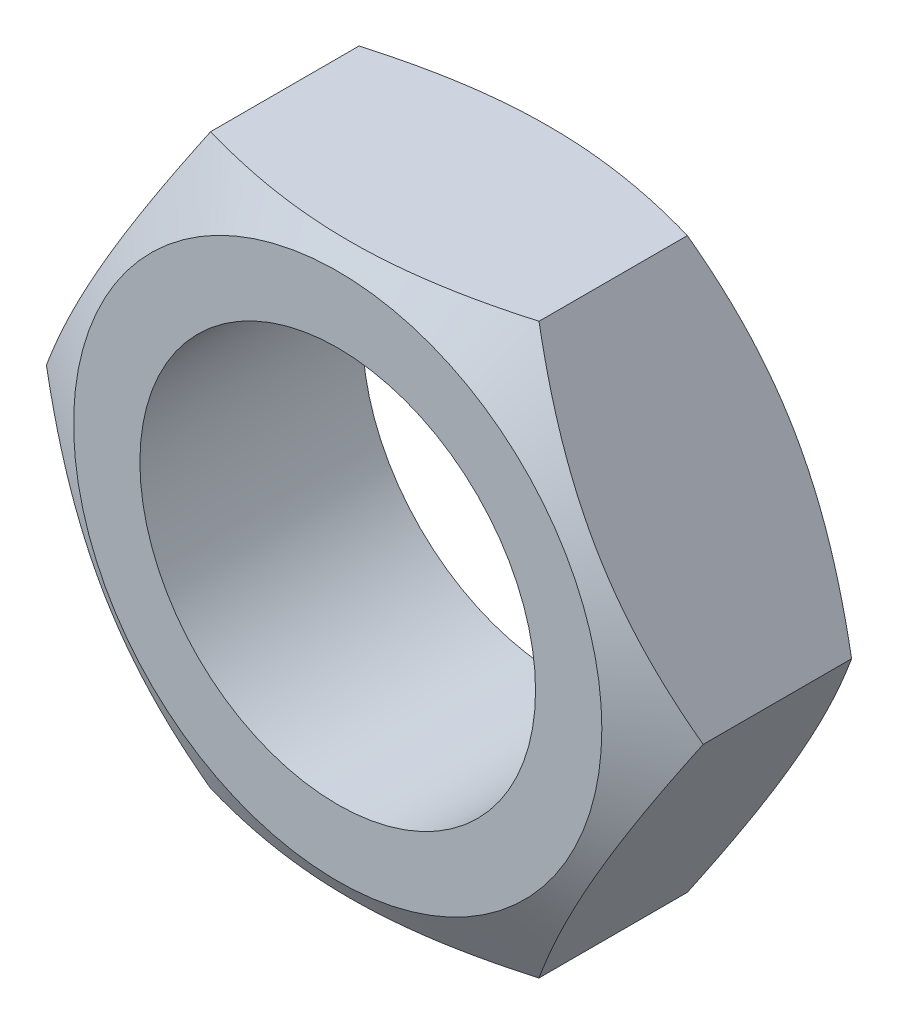
SolidWorks part; units mm, degrees
ref_plane "前视" through (0, 0, 0) normal (0, 0, 1) x (1, 0, 0)
ref_plane "上视" through (0, 0, 0) normal (0, 1, 0) x (1, 0, 0)
ref_plane "右视" through (0, 0, 0) normal (1, 0, 0) x (0, 0, -1)
sketch "草图1" plane through (0, 0, 0) normal (0, 0, 1) x (1, 0, 0)
  line L1 (26.5581, 0) -> (13.2791, 23)
  line L2 (13.2791, 23) -> (-13.2791, 23)
  line L3 (-13.2791, 23) -> (-26.5581, 0)
  line L4 (-26.5581, 0) -> (-13.2791, -23)
  line L5 (-13.2791, -23) -> (13.2791, -23)
  line L6 (13.2791, -23) -> (26.5581, 0)
  circle A0 centre (0, 0) radius 23 construction
  dimension "D1" = 46
extrude "拉伸1" add sketch "草图1" along normal blind 18
sketch "草图2" plane through (0, 0, 0) normal (0, 1, 0) x (1, 0, 0)
  line L0 (-18.9103, -3) -> (18.2967, -3) construction
  line L1 (-18.9103, -9) -> (18.2967, -9) construction
  line L2 (26.5581, -18) -> (26.5581, 0) construction
  line L3 (26.5581, -18) -> (26.5581, 0) construction
  line L4 (4.2098, 9.9028) -> (26.5581, -3)
  line L5 (26.5581, -3) -> (32.1413, 6.6703)
  line L6 (32.1413, 6.6703) -> (4.2098, 9.9028)
  line L7 (26.5581, -15) -> (32.1413, -24.6703)
  line L8 (4.2098, -27.9028) -> (26.5581, -15)
  line L9 (32.1413, -24.6703) -> (4.2098, -27.9028)
  line L10 (0, 13.3063) -> (0, -27.2012) construction
  dimension "D1" = 3
  dimension "D2" = 9
  dimension "D3" = 30
revolve "切除-旋转1" cut sketch "草图2" angle 360 about L10
hole_wizard "M20x2.5 螺纹孔1" positions "3D草图1" profile "草图3" tap size "M20x2.5" standard "ISO"
sketch3d "3D草图1"
  point P0 (0, 0, 18)
sketch "草图3" plane through (0, 0, 18) normal (1, 0, 0) x (0, -1, 0)
  line L0 (0, 0) -> (0, 57.1138)
  line L1 (0, 57.1138) -> (16, 47.5)
  line L2 (16, 47.5) -> (16, 0)
  line L5 (16, 0) -> (0, 0)
  line L10 (0, 57.1138) -> (-16, 47.5) construction
  line L11 (0, -6.35) -> (0, 107.95) construction
  dimension "蹟恇謂郰芛眻噤" = 32
  dimension "蹟恇謂郰芛旮僅" = 47.5
  dimension "絳芛褒僅" = 118
cosmetic thread "孔螺蚊线1" parameters "D1"=18, "D2"=36
